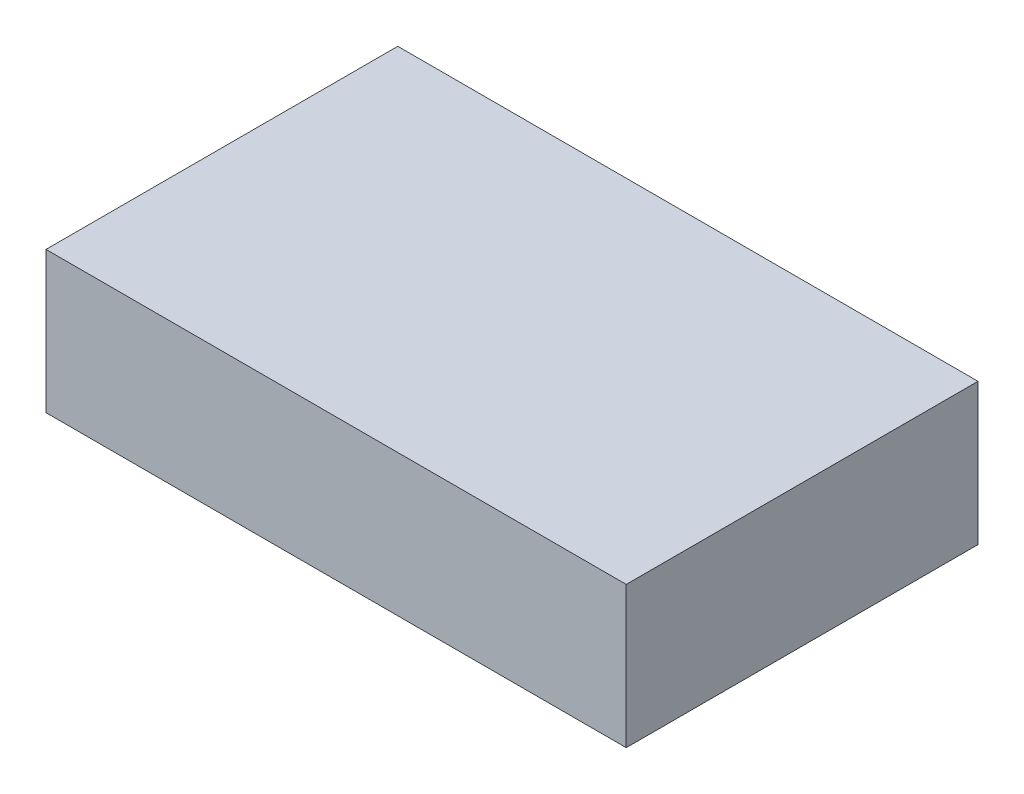
SolidWorks part; units mm, degrees
ref_plane "Front Plane" through (0, 0, 0) normal (0, 0, 1) x (1, 0, 0)
ref_plane "Top Plane" through (0, 0, 0) normal (0, 1, 0) x (1, 0, 0)
ref_plane "Right Plane" through (0, 0, 0) normal (1, 0, 0) x (0, 0, -1)
sketch "Sketch1" plane through (0, 0, 0) normal (0, 1, 0) x (1, 0, 0)
  line L1 (-80, -48.5) -> (80, -48.5)
  line L2 (-80, -48.5) -> (-80, 48.5)
  line L3 (-80, 48.5) -> (80, 48.5)
  line L4 (80, -48.5) -> (80, 48.5)
  line L5 (-80, -48.5) -> (80, 48.5) construction
  line L6 (-80, 48.5) -> (80, -48.5) construction
  point P0 (0, 0)
  dimension "D1" = 160
  dimension "D2" = 97
extrude "Boss-Extrude1" add sketch "Sketch1" along normal blind 39
